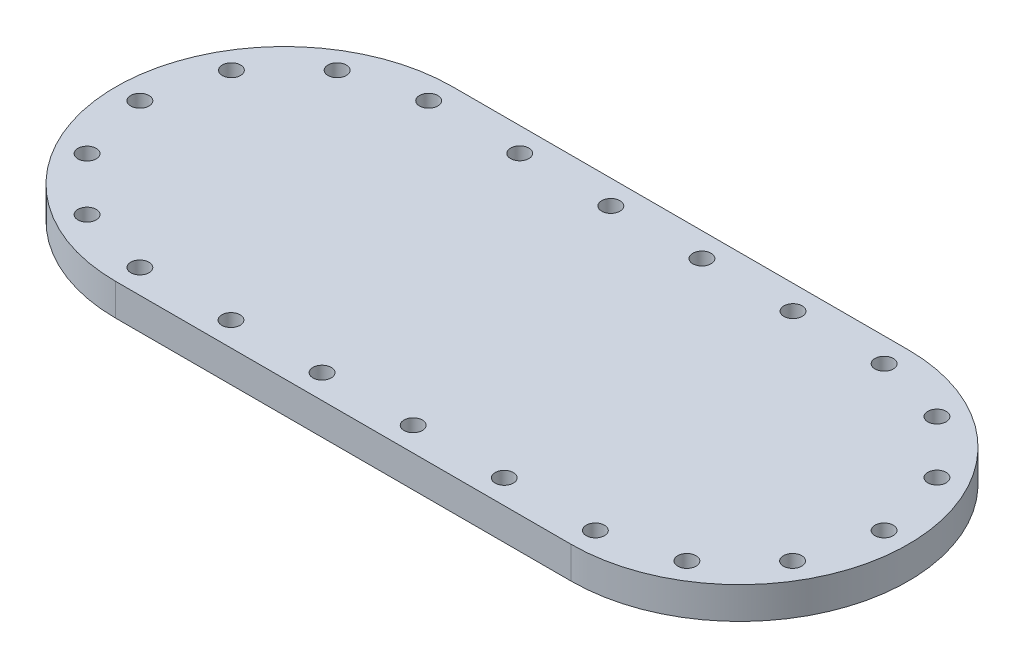
SolidWorks part; units mm, degrees
material "Acrylic (Medium-high impact)"
ref_plane "Front Plane" through (0, 0, 0) normal (0, 0, 1) x (1, 0, 0)
ref_plane "Top Plane" through (0, 0, 0) normal (0, 1, 0) x (1, 0, 0)
ref_plane "Right Plane" through (0, 0, 0) normal (1, 0, 0) x (0, 0, -1)
sketch "Sketch1" plane through (0, 0, 0) normal (0, 1, 0) x (1, 0, 0)
  line L3 (-63.5, 46.99) -> (63.5, 46.99)
  line L4 (-63.5, -46.99) -> (63.5, -46.99)
  arc A2 (63.5, -46.99) -> (63.5, 46.99) centre (63.5, 0) ccw
  arc A3 (-63.5, 46.99) -> (-63.5, -46.99) centre (-63.5, 0) ccw
  point P42 (-63.5, 0)
  point P51 (-63.5, 0)
  point P53 (63.5, 0)
  dimension "D1" = 127
  dimension "D2" = 93.98
extrude "Boss-Extrude1" add sketch "Sketch1" along normal blind 8.89
sketch "Sketch4" plane through (0, 0, 0) normal (0, -1, 0) x (1, 0, 0)
  circle A0 centre (83.6295, -34.8653) radius 2.5527 construction
  circle A1 centre (63.5, -40.259) radius 2.5527 construction
  circle A2 centre (38.1, -40.259) radius 2.5527 construction
  circle A3 centre (12.7, -40.259) radius 2.5527 construction
  circle A4 centre (-12.7, -40.259) radius 2.5527 construction
  circle A5 centre (-38.1, -40.259) radius 2.5527 construction
  circle A6 centre (-63.5, -40.259) radius 2.5527 construction
  circle A7 centre (-83.6295, -34.8653) radius 2.5527 construction
  circle A8 centre (-98.3653, -20.1295) radius 2.5527 construction
  circle A9 centre (-103.759, 0) radius 2.5527 construction
  circle A10 centre (-98.3653, 20.1295) radius 2.5527 construction
  circle A11 centre (-83.6295, 34.8653) radius 2.5527 construction
  circle A12 centre (-63.5, 40.259) radius 2.5527 construction
  circle A13 centre (-38.1, 40.259) radius 2.5527 construction
  circle A14 centre (-12.7, 40.259) radius 2.5527 construction
  circle A15 centre (12.7, 40.259) radius 2.5527 construction
  circle A16 centre (38.1, 40.259) radius 2.5527 construction
  circle A17 centre (63.5, 40.259) radius 2.5527 construction
  circle A18 centre (83.6295, 34.8653) radius 2.5527 construction
  circle A19 centre (98.3653, 20.1295) radius 2.5527 construction
  circle A20 centre (103.759, 0) radius 2.5527 construction
  circle A21 centre (98.3653, -20.1295) radius 2.5527 construction
  circle A22 centre (83.6295, -34.8653) radius 2.5527
  circle A23 centre (63.5, -40.259) radius 2.5527
  circle A24 centre (38.1, -40.259) radius 2.5527
  circle A25 centre (12.7, -40.259) radius 2.5527
  circle A26 centre (-12.7, -40.259) radius 2.5527
  circle A27 centre (-38.1, -40.259) radius 2.5527
  circle A28 centre (-63.5, -40.259) radius 2.5527
  circle A29 centre (-83.6295, -34.8653) radius 2.5527
  circle A30 centre (-98.3653, -20.1295) radius 2.5527
  circle A31 centre (-103.759, 0) radius 2.5527
  circle A32 centre (-98.3653, 20.1295) radius 2.5527
  circle A33 centre (-83.6295, 34.8653) radius 2.5527
  circle A34 centre (-63.5, 40.259) radius 2.5527
  circle A35 centre (-38.1, 40.259) radius 2.5527
  circle A36 centre (-12.7, 40.259) radius 2.5527
  circle A37 centre (12.7, 40.259) radius 2.5527
  circle A38 centre (38.1, 40.259) radius 2.5527
  circle A39 centre (63.5, 40.259) radius 2.5527
  circle A40 centre (83.6295, 34.8653) radius 2.5527
  circle A41 centre (98.3653, 20.1295) radius 2.5527
  circle A42 centre (103.759, 0) radius 2.5527
  circle A43 centre (98.3653, -20.1295) radius 2.5527
extrude "Cut-Extrude1" cut sketch "Sketch4" against normal through all
